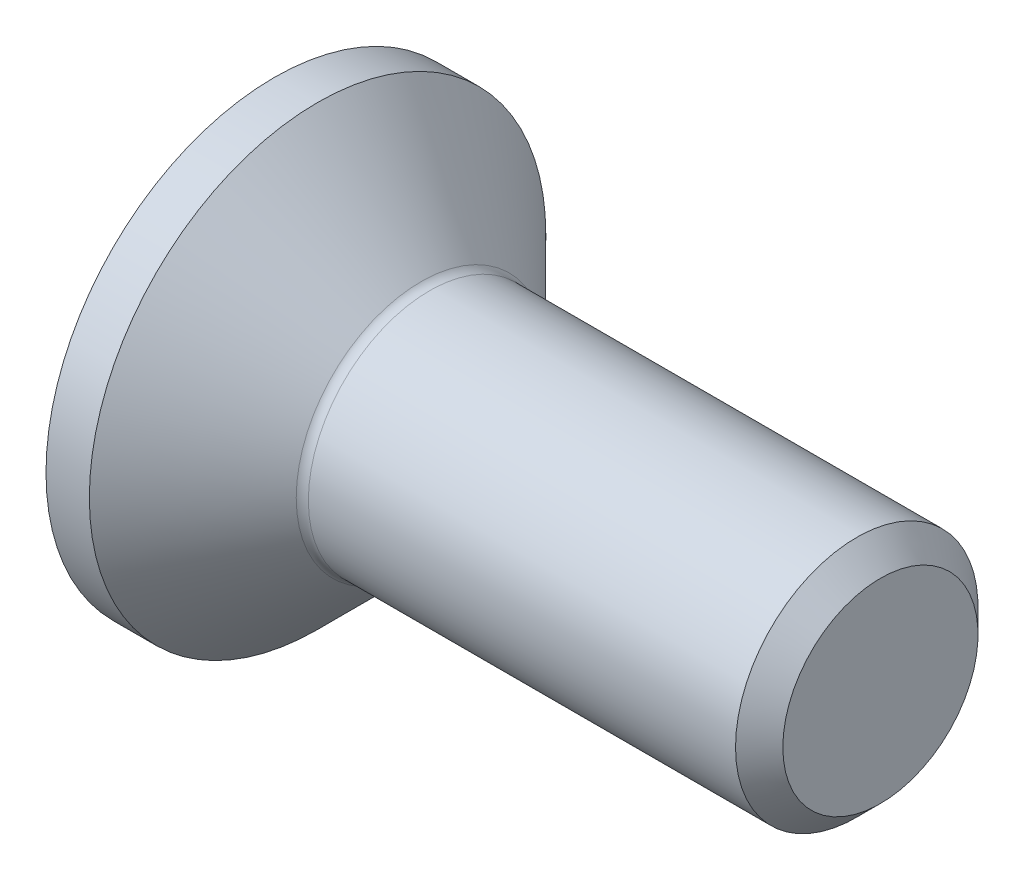
SolidWorks part; units mm, degrees
ref_plane "Plane1" through (0, 0, 0) normal (0, 0, 1) x (1, 0, 0)
ref_plane "Plane2" through (0, 0, 0) normal (0, 1, 0) x (1, 0, 0)
ref_plane "Plane3" through (0, 0, 0) normal (1, 0, 0) x (0, 0, -1)
sketch "BodySke" plane through (0, 0, 0) normal (0, 0, 1) x (1, 0, 0)
  line L0 (0, 0) -> (0, 3.765)
  line L1 (0.715, 3.765) -> (2.48, 2)
  line L2 (0, 3.765) -> (0.715, 3.765)
  line L3 (2.48, 2) -> (9.61, 2)
  line L4 (10, 1.61) -> (10, 0)
  line L5 (10, 0) -> (0, 0)
  line L6 (0, 0) -> (127, 0) construction
  line L7 (0.715, -3.765) -> (2.48, -2) construction
  line L8 (10, 1.61) -> (9.61, 2)
  line L9 (0, -3.765) -> (0.715, -3.765) construction
  line L10 (10, -1.61) -> (9.61, -2) construction
  line L11 (3.18, 8.35) -> (3.18, -13.875) construction
  line L12 (0, 19.05) -> (0, -3.175) construction
  dimension "D1" = 0.715
  dimension "Diameter" = 4
  dimension "Head_ht" = 2.48
  dimension "Length" = 10
  dimension "Body_ch_ang" = 45
  dimension "Head_dia" = 7.53
  dimension "Minor_dia" = 3.22
  dimension "Head_ang" = 90
  dimension "Advance" = 0.7
  dimension "Thread_nom" = 10
revolve "BaseBody" add sketch "BodySke"
cosmetic thread "ThreadCosmetic"
fillet "Fillet1" radius 0.2 1 edges at (2.48, 0, 2)
sketch "Sketch2" plane through (0, 0, 0) normal (0, 0, 1) x (1, 0, 0)
  line L0 (0, 1.25) -> (1.5, 1.25)
  line L1 (1.5, 1.25) -> (2.2217, 0)
  line L2 (0, 0) -> (127, 0) construction
  line L3 (2.2217, 0) -> (0, 0)
  line L4 (0, 0) -> (0, 1.25)
  line L5 (0, -1.25) -> (1.5, -1.25) construction
  line L6 (0, 0) -> (47.625, 0) construction
  line L8 (0, 3.765) -> (0, -3.765) construction
  dimension "D2" = 60
  dimension "PreBroach_depth" = 1.5
  dimension "PreBroach_dia" = 2.5
revolve "PreBroach" cut sketch "Sketch2" angle 360 about L6
sketch "Sketch3" plane through (0, 0, 0) normal (-1, 0, 0) x (0, 0, 1)
  line L0 (-1.25, -0.7217) -> (-1.25, 0.7217)
  line L1 (-1.25, 0.7217) -> (0, 1.4434)
  line L2 (0, 1.4434) -> (1.25, 0.7217)
  line L3 (1.25, 0.7217) -> (1.25, -0.7217)
  line L4 (1.25, -0.7217) -> (0, -1.4434)
  line L5 (0, -1.4434) -> (-1.25, -0.7217)
  dimension "D1" = 1.25
  dimension "D2" = 1.25
  dimension "D3" = 2.5
  dimension "Hex_size" = 2.5
extrude "Hex" cut sketch "Sketch3" against normal blind 1.5
sketch "ThdSchSke" plane through (0, 0, 0) normal (0, 0, 1) x (1, 0, 0)
  line L0 (4.58, -1.61) -> (4.3069, -2)
  line L1 (4.58, -1.61) -> (4.8531, -2)
  line L2 (4.8531, -2) -> (4.8531, -2.5)
  line L3 (-3.175, 0) -> (5.1513, 0) construction
  line L4 (0, 3.765) -> (0, -3.765) construction
  line L5 (4.8531, -2.5) -> (4.3069, -2.5)
  line L6 (4.3069, -2.5) -> (4.3069, -2)
  dimension "Thread_minor" = 3.22
  dimension "Diameter" = 4
  dimension "Start" = 4.58
  dimension "SideAngle" = 55
  dimension "VeeAngle" = 70
  dimension "Overcut" = 5
revolve "ThreadSchematic" [suppressed] cut sketch "ThdSchSke" angle 360 about L3
pattern_linear "ThdSchPat" [suppressed]
equation "\"Thread_minor@ThreadCosmetic\"  =  \"Minor_dia@BodySke\""
equation "\"D1@Sketch3\" = \"Hex_size@Sketch3\" / 2"
equation "\"D2@Sketch3\" = \"D1@Sketch3\""
equation "\"D3@Sketch3\" = \"Hex_size@Sketch3\""
equation "\"Thread_length@ThreadCosmetic\" = ((sgn( (\"Length@BodySke\" - \"Advance@BodySke\" * 3.0 - \"Head_ht@BodySke\" ) - \"Thread_nom@BodySke\" )-1)*( (\"Length@BodySke\" - \"Advance@BodySke\" * 3.0 - \"Head_ht@BodySke\" ) - \"Thread_nom@BodySke\" ))/-2+ \"Thread_nom@BodySke\""
equation "\"Thread_minor@ThdSchSke\" = \"Minor_dia@BodySke\""
equation "\"Diameter@ThdSchSke\" = \"Diameter@BodySke\""
equation "\"Overcut@ThdSchSke\" = \"Diameter@BodySke\" * 1.25"
equation "\"Start@ThdSchSke\" = 0.000001 + \"Length@BodySke\" - \"Thread_length@ThreadCosmetic\"  '---Countersunk---"
equation "\"Num_threads@ThdSchPat\" = int( \"Thread_length@ThreadCosmetic\" / \"Advance@BodySke\" + 0.999 )  + 1"
equation "\"Advance@ThdSchPat\" = \"Thread_length@ThreadCosmetic\" /  (\"Num_threads@ThdSchPat\" - 1) 'relax it"
equation "\"Num_threads@ThdSchPat\" = \"Num_threads@ThdSchPat\" - sgn( \"Num_threads@ThdSchPat\" - 1) '---chamfered tips only---"
